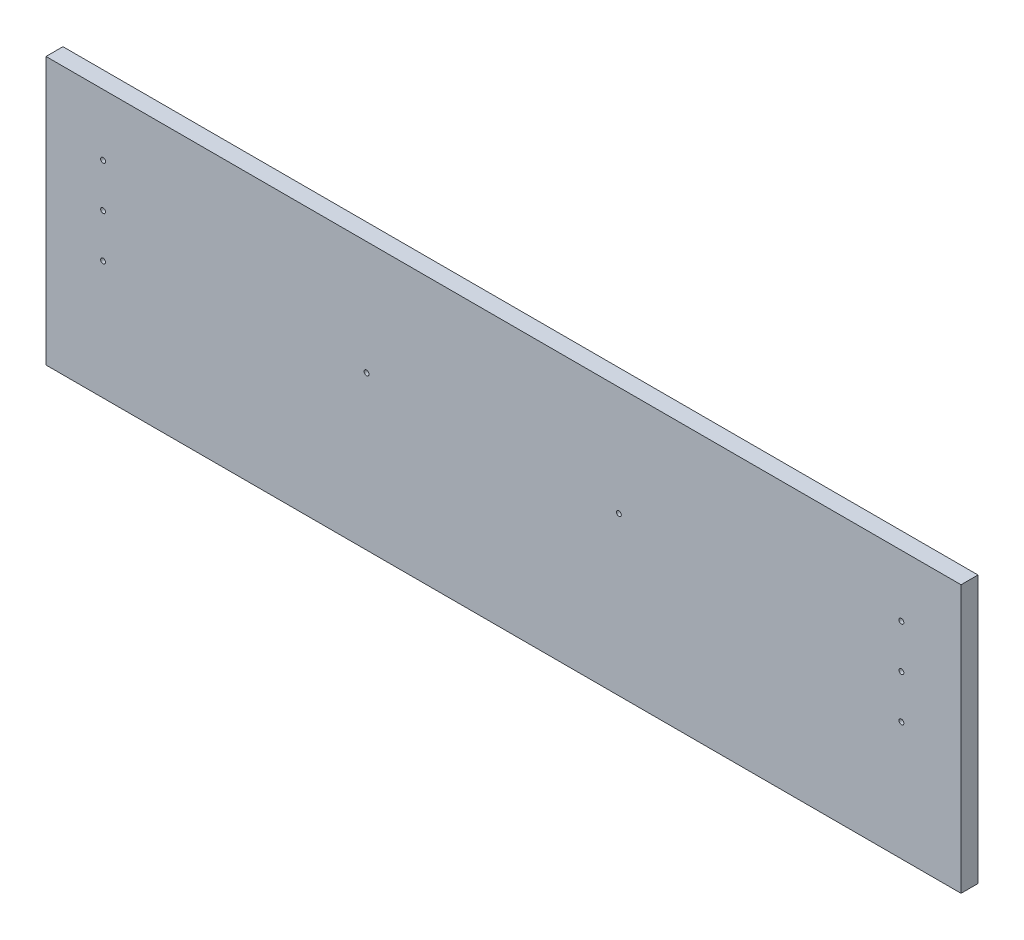
SolidWorks part; units mm, degrees
ref_plane "Front Plane" through (0, 0, 0) normal (0, 0, 1) x (1, 0, 0)
ref_plane "Top Plane" through (0, 0, 0) normal (0, 1, 0) x (1, 0, 0)
ref_plane "Right Plane" through (0, 0, 0) normal (1, 0, 0) x (0, 0, -1)
sketch "Sketch1" plane through (0, 0, 0) normal (0, 0, 1) x (1, 0, 0)
  line L1 (-1865.9199, 503.736) -> (-840.4586, 503.736)
  line L2 (-1865.9199, 503.736) -> (-1865.9199, 803.236)
  line L3 (-1865.9199, 803.236) -> (-840.4586, 803.236)
  line L4 (-840.4586, 503.736) -> (-840.4586, 803.236)
  line L6 (-928.1289, 703.236) -> (-1785.9199, 703.236) construction
  line L7 (-928.1289, 703.236) -> (-1785.9199, 703.236) construction
  dimension "D1" = 100
extrude "Boss-Extrude1" add sketch "Sketch1" along normal blind 19
sketch "Sketch2" plane through (0, 0, 0) normal (0, 0, -1) x (-1, 0, 0)
  line L0 (887.3199, 576.496) -> (966.4873, 576.506) construction
  line L1 (887.3199, 576.496) -> (887.3199, 714.236) construction
  line L2 (887.3199, 714.236) -> (942.25, 714.236)
  point P0 (907.3199, 694.236)
  point P1 (907.3199, 643.1464)
  point P2 (907.3199, 596.4985)
  dimension "D1" = 20
  dimension "D2" = 20
  dimension "D3" = 20
sketch "Sketch7" plane through (0, 0, 0) normal (0, 0, -1) x (-1, 0, 0)
  line L0 (926.5757, 714.236) -> (887.3199, 714.236) construction
  line L1 (887.3199, 714.236) -> (887.3099, 576.506) construction
  line L2 (887.3099, 576.506) -> (916.3736, 576.506) construction
  line L3 (1760.6398, 576.506) -> (1824.3378, 576.506) construction
  line L4 (1824.3378, 576.506) -> (1824.3378, 713.069) construction
  line L5 (1824.3378, 713.069) -> (1760.6291, 713.069) construction
  point P3 (907.3113, 596.506)
  point P5 (907.3113, 645.371)
  point P6 (907.3113, 694.236)
  point P8 (887.3149, 645.371)
  point P12 (1803.6883, 596.506)
  point P13 (1811.0963, 644.7875)
  point P14 (1804.0368, 693.069)
  point P15 (1824.3378, 644.7875)
  dimension "D1" = 20
  dimension "D2" = 20
  dimension "D3" = 20
  dimension "D4" = 20
  dimension "D5" = 20
sketch "Sketch8" plane through (0, 0, 0) normal (0, 0, -1) x (-1, 0, 0)
  line L0 (924.0695, 754.4709) -> (887.3299, 754.4609) construction
  line L1 (887.3299, 754.4609) -> (887.3199, 616.7309) construction
  line L2 (887.3199, 616.7309) -> (924.0595, 616.7409) construction
  line L3 (1789.4528, 754.4709) -> (1816.9515, 754.4709) construction
  line L4 (1816.9515, 754.4709) -> (1816.9415, 616.7309) construction
  line L5 (1816.9415, 616.7309) -> (1790.8891, 616.7309) construction
  point P2 (907.3213, 734.4663)
  point P5 (907.3213, 685.5959)
  point P6 (907.3213, 636.7363)
  point P8 (1801.943, 636.7309)
  point P10 (1801.943, 685.6009)
  point P11 (887.3249, 685.5959)
  point P14 (1801.943, 734.4663)
  point P15 (0, 0)
  point P16 (0, 0)
  point P17 (1816.9465, 685.6009)
  point P18 (0, 0)
  dimension "D1" = 20
  dimension "D2" = 20
  dimension "D3" = 20
  dimension "D4" = 20
  dimension "D5" = 15
  dimension "D6" = 20.0046
hole_wizard "M5 Clearance Hole1" positions "Sketch9" profile "Sketch10" hole size "M5" standard "ISO"
sketch "Sketch9" plane through (-1324.1983, -38.2529, 0) normal (0, 0, -1) x (1, 0, 0)
  point P0 (-477.7447, -772.7192)
  point P3 (-477.7447, -723.8537)
  point P6 (-477.7447, -674.9837)
  point P9 (416.877, -772.7192)
  point P12 (416.877, -723.8487)
  point P15 (416.877, -674.9892)
  point P18 (100.2351, -718.9325)
  point P20 (-182.4777, -714.0157)
sketch "Sketch10" plane through (-1801.943, 734.4663, 0) normal (1, 0, 0) x (0, 1, 0)
  line L0 (0, 0) -> (0, 34)
  line L1 (0, 34) -> (2.75, 32.3476)
  line L2 (2.75, 32.3476) -> (2.75, 0)
  line L3 (2.75, 0) -> (0, 0)
  line L4 (0, 34) -> (-2.75, 32.3476) construction
  line L5 (0, -6.35) -> (0, 107.95) construction
  dimension "Hole Dia." = 5.5
  dimension "Hole Depth" = 34
  dimension "Drill Angle" = 118
